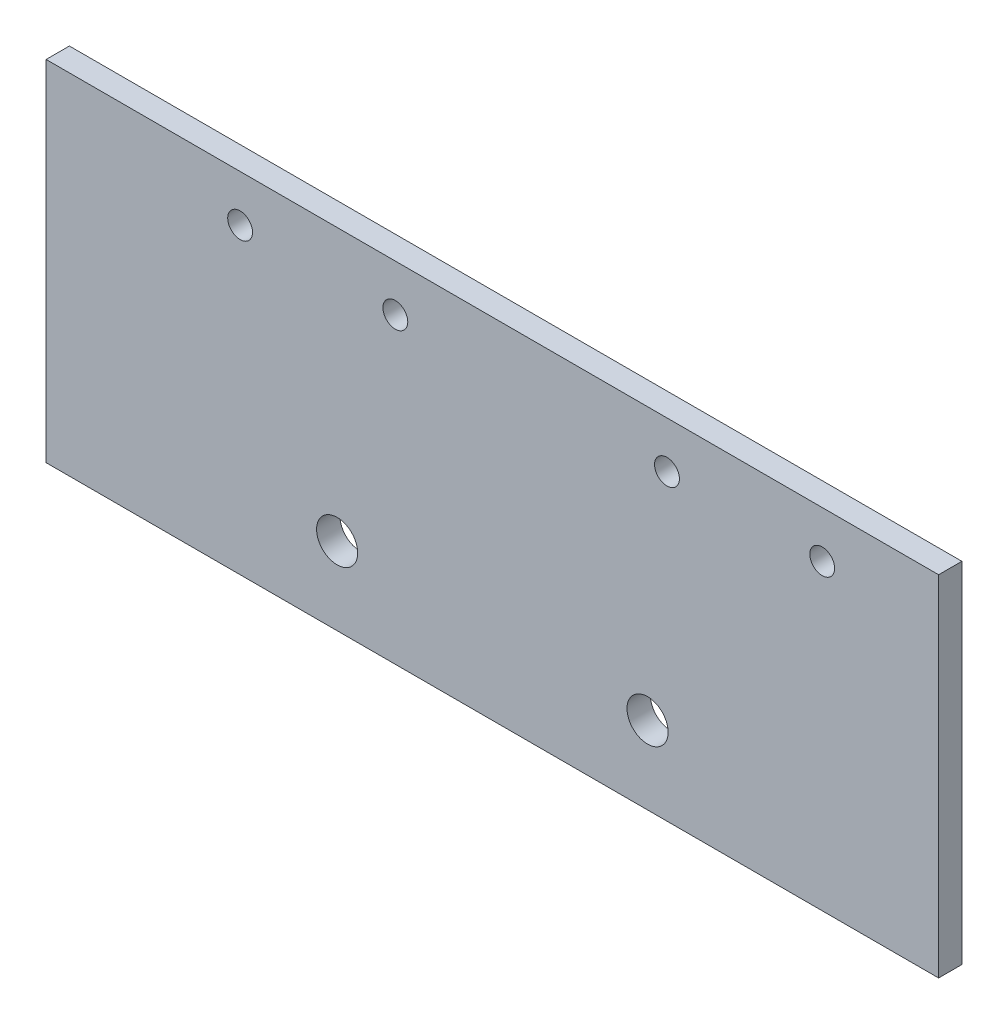
SolidWorks part; units mm, degrees
ref_plane "前视基准面" through (0, 0, 0) normal (0, 0, 1) x (1, 0, 0)
ref_plane "上视基准面" through (0, 0, 0) normal (0, 1, 0) x (1, 0, 0)
ref_plane "右视基准面" through (0, 0, 0) normal (1, 0, 0) x (0, 0, -1)
other "Configuration Table"
sketch "草图1" plane through (0, 0, 0) normal (0, 0, 1) x (1, 0, 0)
  line L1 (-219.5, 20) -> (-219.5, -13.8147) construction
  line L2 (-209.5, 20) -> (-229.5, 20) construction
  line L3 (-209.5, 0) -> (-189.5, 0) construction
  line L4 (-257, 45) -> (-182, 45)
  line L5 (-257, 45) -> (-257, 0)
  line L6 (-257, 0) -> (-182, 0)
  line L7 (-182, 45) -> (-182, 0)
  line L8 (-257, 45) -> (-182, 0) construction
  line L9 (-257, 0) -> (-182, 45) construction
  line L10 (-229.5, 20) -> (-229.5, 0) construction
  line L11 (-229.5, 20) -> (-229.5, 0) construction
  line L12 (-249.5, 20) -> (-249.5, 0) construction
  line L13 (-249.5, 20) -> (-249.5, 0) construction
  line L14 (-239.5, 20) -> (-239.5, 0) construction
  line L15 (-229.5, 20) -> (-249.5, 20) construction
  line L16 (-249.5, 0) -> (-229.5, 0) construction
  circle A0 centre (-239.5, 10) radius 2.65
  circle A1 centre (-199.5, 10) radius 2.65
  point P8 (-219.5, 22.5)
  dimension "D2" = 5.3
  dimension "D1" = 75
  dimension "D3" = 45
extrude "凸台-拉伸1" add sketch "草图1" along normal blind 3
sketch "草图2" plane through (0, 0, 3) normal (0, 0, 1) x (1, 0, 0)
  line L0 (-60, 0) -> (-379, 0) construction
  line L1 (-182, 45) -> (-162, 45)
  line L2 (-182, 45) -> (-182, 0)
  line L3 (-182, 0) -> (-162, 0)
  line L4 (-162, 45) -> (-162, 0)
  line L5 (-182, 45) -> (-162, 0) construction
  line L6 (-182, 0) -> (-162, 45) construction
  point P4 (-172, 22.5)
  dimension "D1" = 20
extrude "凸台-拉伸2" add sketch "草图2" against normal up to surface (3 mm away) up to face at (-219.5, 22.5, 0)
sketch "草图3" plane through (0, 0, 3) normal (0, 0, 1) x (1, 0, 0)
  line L4 (-202, 42) -> (-202, 36)
  line L5 (-162, 42) -> (-202, 42)
  line L6 (-162, 36) -> (-162, 42)
  line L7 (-202, 36) -> (-162, 36)
  line L9 (-162, 42) -> (-202, 42)
  line L10 (-162, 36) -> (-162, 42)
  circle A0 centre (-177, 39) radius 1.6 construction
  circle A1 centre (-177, 39) radius 1.6
  circle A2 centre (-197, 39) radius 1.6 construction
  circle A3 centre (-197, 39) radius 1.6
  circle A4 centre (-232, 39) radius 1.6 construction
  circle A5 centre (-232, 39) radius 1.6
  circle A6 centre (-252, 39) radius 1.6 construction
  circle A7 centre (-252, 39) radius 1.6
  dimension "D1" = 0
extrude "切除-拉伸1" cut sketch "草图3" against normal blind 3 contours A3 | A1 | A5 | A7
sketch "草图4" plane through (0, 0, 3) normal (0, 0, 1) x (1, 0, 0)
  line L0 (-257, 45) -> (-277, 45)
  line L1 (-277, 45) -> (-277, 0)
  line L2 (-60, 0) -> (-379, 0) construction
  line L3 (-277, 0) -> (-257, 0)
  line L4 (-257, 0) -> (-257, 45)
  dimension "D1" = 20
extrude "凸台-拉伸3" add sketch "草图4" against normal up to surface (3 mm away) up to face at (-250.4, 39, 0)
